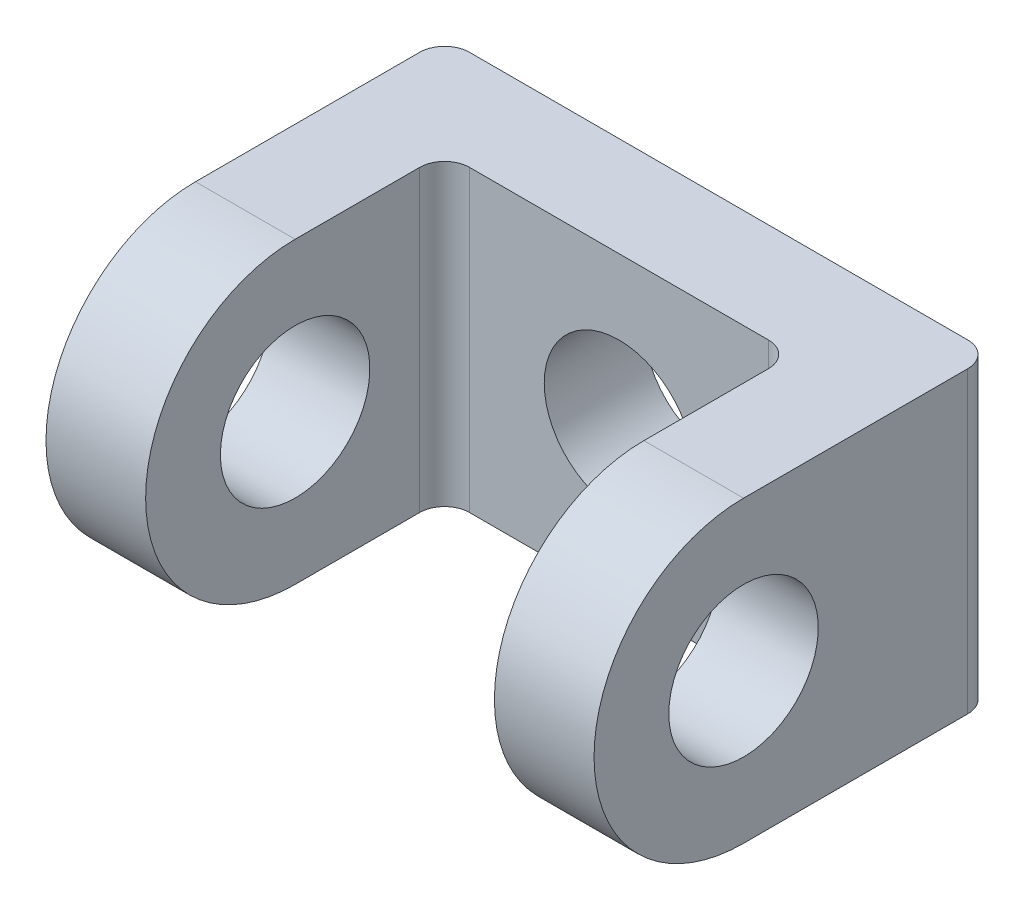
SolidWorks part; units mm, degrees
material "ESUN PLA +"
ref_plane "Front Plane" through (0, 0, 0) normal (0, 0, 1) x (1, 0, 0)
ref_plane "Top Plane" through (0, 0, 0) normal (0, 1, 0) x (1, 0, 0)
ref_plane "Right Plane" through (0, 0, 0) normal (1, 0, 0) x (0, 0, -1)
sketch "Sketch1" plane through (0, 0, 0) normal (1, 0, 0) x (0, 0, -1)
  line L0 (0, 30) -> (50, 30)
  line L1 (50, 30) -> (50, -30)
  line L2 (50, -30) -> (0, -30)
  arc A0 (0, 30) -> (0, -30) centre (0, 0) ccw
  arc A1 (0, -30) -> (0, 30) centre (0, 0) ccw construction
  dimension "D1" = 60
  dimension "D2" = 50
extrude "Boss-Extrude1" add sketch "Sketch1" along normal mid plane 110
sketch "Sketch2" plane through (0, 0, 0) normal (0, 1, 0) x (1, 0, 0)
  line L0 (-55, -30) -> (55, -30) construction
  line L1 (-35, 30) -> (35, 30)
  line L2 (-35, 30) -> (-35, -30)
  line L3 (-35, -30) -> (35, -30)
  line L4 (35, 30) -> (35, -30)
  line L5 (-55, 50) -> (-55, 0) construction
  line L6 (55, 50) -> (55, 0) construction
  line L7 (55, 50) -> (-55, 50) construction
  dimension "D1" = 20
  dimension "D2" = 20
  dimension "D3" = 20
extrude "Cut-Extrude1" cut sketch "Sketch2" against normal through all both and the other way through all
sketch "Sketch5" plane through (-55, 0, 0) normal (-1, 0, 0) x (0, 0, 1)
  circle A1 centre (0, 0) radius 15
  dimension "D1" = 30
extrude "Cut-Extrude4" cut sketch "Sketch5" against normal through all both and the other way through all
fillet "Fillet1" radius 5 4 edges at (55, 0, -50) (35, 0, -30) (-35, 0, -30) (-55, 0, -50)
sketch "Sketch6" plane through (0, 0, -30) normal (0, 0, 1) x (1, 0, 0)
  circle A0 centre (0, 0) radius 15
  dimension "D1" = 30
extrude "Cut-Extrude5" cut sketch "Sketch6" against normal through all both and the other way through all
